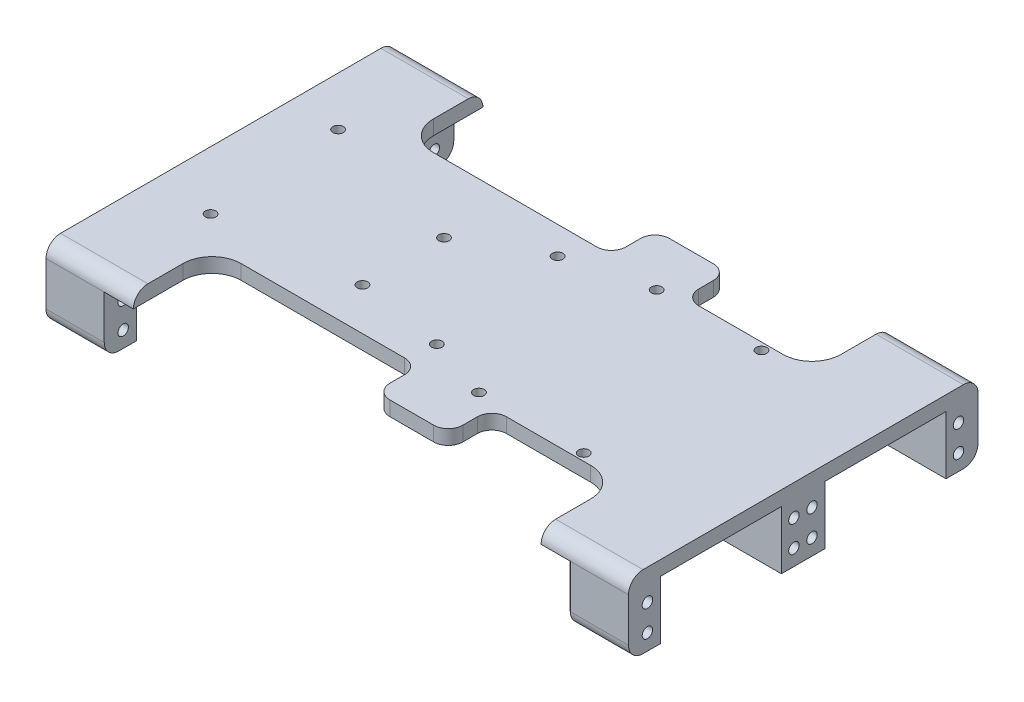
SolidWorks part; units mm, degrees
ref_plane "Front" through (0, 0, 0) normal (0, 0, 1) x (1, 0, 0)
ref_plane "Top" through (0, 0, 0) normal (0, 1, 0) x (1, 0, 0)
ref_plane "Right" through (0, 0, 0) normal (1, 0, 0) x (0, 0, -1)
sketch "스케치1" plane through (0, 0, 0) normal (0, 1, 0) x (1, 0, 0)
  line L0 (100, 0) -> (-100, 0) construction
  line L1 (-100, 60) -> (-70, 60)
  line L2 (-100, 60) -> (-100, -60)
  line L3 (-100, -60) -> (-70, -60)
  line L4 (100, 60) -> (100, -60)
  line L5 (-100, 60) -> (100, -60) construction
  line L6 (-100, -60) -> (100, 60) construction
  line L7 (-70, -33) -> (70, -33)
  line L8 (-70, -33) -> (-70, -60)
  line L10 (70, -33) -> (70, -60)
  line L11 (-70, -33) -> (2.0805, -71.7583) construction
  line L12 (2.0805, -71.7583) -> (70, -33) construction
  line L13 (70, -60) -> (100, -60)
  line L14 (70, 33) -> (70, 60)
  line L15 (-70, 33) -> (-70, 60)
  line L16 (-70, 33) -> (70, 33)
  line L17 (70, 60) -> (100, 60)
  point P0 (0, 0)
  point P6 (2.0805, -71.7583)
  dimension "D1" = 200
  dimension "D2" = 120
  dimension "D3" = 30
  dimension "D4" = 30
  dimension "D5" = 27
extrude "보스-돌출1" add sketch "스케치1" along normal blind 5
sketch "스케치3" plane through (0, 0, 0) normal (0, -1, 0) x (1, 0, 0)
  line L0 (-100, 0) -> (100, 0) construction
  line L1 (-100, -60) -> (-100, 60) construction
  line L3 (-100, -7.5) -> (-80, -7.5)
  line L4 (-100, 60) -> (-80, 60)
  line L5 (-100, 60) -> (-100, 49)
  line L6 (-100, 49) -> (-80, 49)
  line L7 (-80, 60) -> (-80, 49)
  line L8 (-100, 7.5) -> (-80, 7.5)
  line L9 (-100, 7.5) -> (-100, -7.5)
  line L10 (-100, 0) -> (-80, 0)
  line L11 (-80, 7.5) -> (-80, -7.5)
  line L16 (100, 60) -> (100, -60) construction
  line L17 (-100, -49) -> (-80, -49)
  line L18 (-85, 60) -> (-85, -60) construction
  line L19 (-100, 60) -> (-70, 60) construction
  line L20 (-70, -60) -> (-100, -60) construction
  line L33 (-80, -60) -> (-80, -49)
  line L34 (-100, -60) -> (-80, -60)
  line L35 (-100, -60) -> (-100, -49)
  line L36 (0, 94.3589) -> (0, -123.8309) construction
  line L37 (85, 60) -> (85, -60) construction
  line L38 (100, -60) -> (100, -49)
  line L39 (100, -60) -> (80, -60)
  line L40 (80, -60) -> (80, -49)
  line L41 (100, -49) -> (80, -49)
  line L42 (80, 7.5) -> (80, -7.5)
  line L43 (100, 0) -> (80, 0)
  line L44 (100, 7.5) -> (100, -7.5)
  line L45 (100, 7.5) -> (80, 7.5)
  line L46 (80, 60) -> (80, 49)
  line L47 (100, 49) -> (80, 49)
  line L48 (100, 60) -> (100, 49)
  line L49 (100, 60) -> (80, 60)
  line L50 (100, -7.5) -> (80, -7.5)
  line M11 (-70, 60) -> (-100, 60)
  line M12 (-100, 60) -> (-100, -60)
  line M13 (-100, -60) -> (-70, -60)
  dimension "D1" = 20
  dimension "D2" = 11
  dimension "D3" = 7.5
  dimension "D4" = 20
extrude "보스-돌출2" add sketch "스케치3" along normal blind 20 contours L7 L6 M11 M12 | L11 L8 L10 M12 | L11 L10 L9 L3 | L33 L17 M13 M12 | L46 L47 L48 L49 | L42 L50 L44 L45 | L38 L41 L40 L39
fillet "필렛1" radius 5 4 edges at (90, -20, 60) (90, -20, -60) (-90, -20, -60) (-90, -20, 60)
fillet "필렛2" radius 5 4 edges at (-85, 5, -60) (85, 5, -60) (85, 5, 60) (-85, 5, 60)
hole_wizard "M3 여유 구멍1" positions "스케치4" profile "스케치6" hole size "M3" standard "KS" end condition through all
sketch "스케치4" plane through (-100, 0, 0) normal (-1, 0, 0) x (0, 0, 1)
  point P0 (-3, -5.5)
  point P3 (-3, -14.5)
  point P6 (3.2, -14.5)
  point P9 (3.2, -5.5)
  point P12 (-53.3, -5.5)
  point P15 (-53.3, -14.5)
  point P18 (53.5, -5.5)
  point P21 (53.5, -14.5)
sketch "스케치6" plane through (-100, -5.5, -3) normal (0, 1, 0) x (0, 0, 1)
  line L0 (0, 0) -> (0, 200)
  line L1 (0, 200) -> (1.8, 200)
  line L2 (1.8, 200) -> (1.8, 0)
  line L5 (1.8, 0) -> (0, 0)
  line L11 (0, -6.35) -> (0, 107.95) construction
  dimension "관통 구멍 지름" = 3.6
  dimension "관통 구멍 깊이" = 200
fillet "필렛3" radius 10 4 edges at (-70, 2.5, -33) (70, 2.5, -33) (70, 2.5, 33) (-70, 2.5, 33)
hole_wizard "M3 여유 구멍2" positions "스케치8" profile "스케치10" hole size "M3" standard "KS" end condition through all
sketch "스케치8" plane through (0, 5, 0) normal (0, 1, 0) x (1, 0, 0)
  line L0 (55.16, 30.5) -> (19.16, 30.5) construction
  line L1 (19.16, 30.5) -> (19.16, -30.5) construction
  line L2 (19.16, -30.5) -> (55.16, -30.5) construction
  line L3 (55.16, -30.5) -> (55.16, 30.5) construction
  line L5 (60, 33) -> (-60, 33) construction
  line L6 (-60, -33) -> (60, -33) construction
  line L7 (56.16, -9.1127) -> (56.16, -35.5) construction
  point P6 (55.16, 30.5)
  point P8 (19.16, 30.5)
  point P10 (19.16, -30.5)
  point P12 (55.16, -30.5)
  point P41 (57.9922, -54.3622)
  dimension "D1" = 2.5
  dimension "D2" = 2.5
  dimension "D3" = 1
  dimension "D4" = 36
sketch "스케치10" plane through (55.16, 5, -30.5) normal (1, 0, 0) x (0, 0, 1)
  line L0 (0, 0) -> (0, 25)
  line L1 (0, 25) -> (1.8, 25)
  line L2 (1.8, 25) -> (1.8, 0)
  line L5 (1.8, 0) -> (0, 0)
  line L11 (0, -6.35) -> (0, 107.95) construction
  dimension "관통 구멍 지름" = 3.6
  dimension "관통 구멍 깊이" = 25
hole_wizard "M3 여유 구멍3" positions "스케치11" profile "스케치12" hole size "M3" standard "KS" end condition through all
sketch "스케치11" plane through (0, 5, 0) normal (0, 1, 0) x (1, 0, 0)
  point P0 (-32.8498, 9.5)
  point P3 (-2.429, -23.3714)
  point P6 (-7.8498, 23.5)
  point P9 (-32.8498, -18.5)
  point P12 (-80, -23.5)
  point P15 (-83.2, 23.5)
sketch "스케치12" plane through (-32.8498, 5, -9.5) normal (1, 0, 0) x (0, 0, 1)
  line L0 (0, 0) -> (0, 25)
  line L1 (0, 25) -> (1.8, 25)
  line L2 (1.8, 25) -> (1.8, 0)
  line L5 (1.8, 0) -> (0, 0)
  line L11 (0, -6.35) -> (0, 107.95) construction
  dimension "관통 구멍 지름" = 3.6
  dimension "관통 구멍 깊이" = 25
sketch "스케치13" plane through (0, 5, 0) normal (0, 1, 0) x (1, 0, 0)
  line L0 (0, 96.3334) -> (0, -79.3089) construction
  line L1 (146.4167, 0) -> (-128.9356, 0) construction
  line L2 (-97, 49) -> (-97, 45)
  line L3 (-94, 42) -> (-92, 42)
  line L4 (-92, 42) -> (-92, 44)
  line L5 (-89, 47) -> (-87, 47)
  line L6 (-87, 47) -> (-87, 49)
  line L7 (-90, 52) -> (-94, 52)
  line L8 (-100, 55) -> (-100, -55) construction
  line L9 (-70, 55) -> (-100, 55) construction
  line L10 (-90, -52) -> (-94, -52)
  line L11 (-87, -47) -> (-87, -49)
  line L12 (-89, -47) -> (-87, -47)
  line L13 (-92, -42) -> (-92, -44)
  line L14 (-94, -42) -> (-92, -42)
  line L15 (-97, -49) -> (-97, -45)
  line L16 (97, -49) -> (97, -45)
  line L17 (94, -42) -> (92, -42)
  line L18 (92, -42) -> (92, -44)
  line L19 (89, -47) -> (87, -47)
  line L20 (87, -47) -> (87, -49)
  line L21 (90, -52) -> (94, -52)
  line L22 (90, 52) -> (94, 52)
  line L23 (87, 47) -> (87, 49)
  line L24 (89, 47) -> (87, 47)
  line L25 (92, 42) -> (92, 44)
  line L26 (94, 42) -> (92, 42)
  line L27 (97, 49) -> (97, 45)
  arc A0 (-87, 49) -> (-90, 52) centre (-90, 49) ccw
  arc A1 (-97, 45) -> (-94, 42) centre (-94, 45) ccw
  arc A2 (-92, 44) -> (-89, 47) centre (-89, 44) cw
  arc A3 (-97, 49) -> (-94, 52) centre (-94, 49) cw
  arc A4 (-97, -49) -> (-94, -52) centre (-94, -49) ccw
  arc A5 (-92, -44) -> (-89, -47) centre (-89, -44) ccw
  arc A6 (-97, -45) -> (-94, -42) centre (-94, -45) cw
  arc A7 (-87, -49) -> (-90, -52) centre (-90, -49) cw
  arc A8 (87, -49) -> (90, -52) centre (90, -49) ccw
  arc A9 (97, -45) -> (94, -42) centre (94, -45) ccw
  arc A10 (92, -44) -> (89, -47) centre (89, -44) cw
  arc A11 (97, -49) -> (94, -52) centre (94, -49) cw
  arc A12 (97, 49) -> (94, 52) centre (94, 49) ccw
  arc A13 (92, 44) -> (89, 47) centre (89, 44) ccw
  arc A14 (97, 45) -> (94, 42) centre (94, 45) cw
  arc A15 (87, 49) -> (90, 52) centre (90, 49) cw
  point P17 (-87, 52)
  point P20 (-97, 42)
  point P25 (-97, 52)
  point P40 (-97, -52)
  point P41 (-97, -42)
  point P42 (-87, -52)
  point P57 (87, -52)
  point P58 (97, -42)
  point P59 (97, -52)
  point P74 (97, 52)
  point P75 (97, 42)
  point P76 (87, 52)
  dimension "D7" = 3
  dimension "D1" = 3
  dimension "D2" = 3
  dimension "D3" = 10
  dimension "D4" = 10
  dimension "D5" = 5
  dimension "D6" = 5
sketch "스케치15" plane through (0, 5, 0) normal (0, 1, 0) x (1, 0, 0)
  line L1 (-60, -33) -> (60, -33) construction
  line L3 (1.1074, -33) -> (26.1074, -33)
  line L4 (1.1074, -33) -> (1.1074, -48)
  line L5 (1.1074, -48) -> (26.1074, -48)
  line L6 (26.1074, -33) -> (26.1074, -48)
  line L7 (0, 0) -> (100, 0) construction
  line L8 (100, -55) -> (100, 55) construction
  line L9 (1.1074, 48) -> (26.1074, 48)
  line L10 (1.1074, 33) -> (1.1074, 48)
  line L11 (1.1074, 33) -> (26.1074, 33)
  line L12 (26.1074, 33) -> (26.1074, 48)
  dimension "D1" = 25
  dimension "D2" = 15
extrude "보스-돌출5" add sketch "스케치15" against normal blind 5
fillet "필렛8" radius 5 8 edges at (1.1074, 2.5, -33) (26.1074, 2.5, -33) (26.1074, 2.5, -48) (1.1074, 2.5, -48) (26.1074, 2.5, 33) (26.1074, 2.5, 48) (1.1074, 2.5, 48) (1.1074, 2.5, 33)
